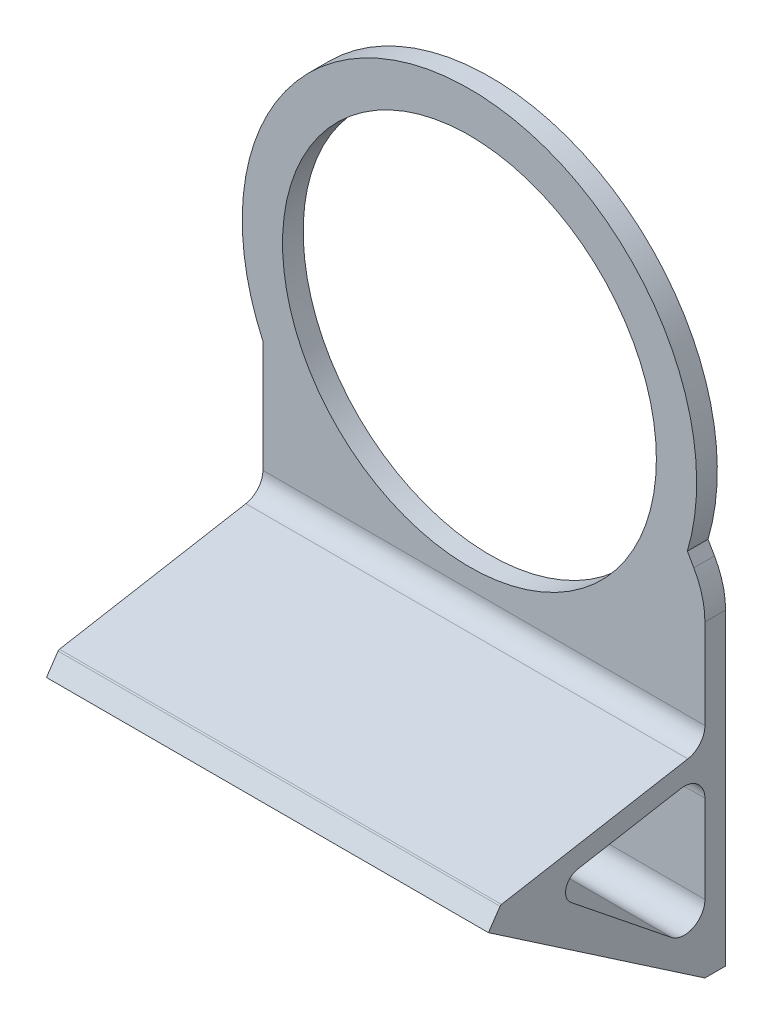
SolidWorks part; units mm, degrees
ref_plane "Plan de face" through (0, 0, 0) normal (0, 0, 1) x (1, 0, 0)
ref_plane "Plan de dessus" through (0, 0, 0) normal (0, 1, 0) x (1, 0, 0)
ref_plane "Plan de droite" through (0, 0, 0) normal (1, 0, 0) x (0, 0, -1)
sketch "Esquisse1" plane through (0, 0, 0) normal (0, 0, 1) x (1, 0, 0)
  circle A0 centre (0, 0) radius 55
  circle A1 centre (0, 0) radius 45.25
  dimension "D1" = 110
  dimension "D2" = 90.5
extrude "Boss.-Extru.1" add sketch "Esquisse1" along normal blind 5
sketch "Esquisse2" plane through (0, 0, 0) normal (0, 0, -1) x (-1, 0, 0)
  line L0 (0, 0) -> (0, -89.0055) construction
  line L1 (-50, -22.9129) -> (-50, -102.9129)
  line L2 (50, -22.9129) -> (50, -102.9129)
  line L3 (-50, -102.9129) -> (50, -102.9129)
  circle A0 centre (0, 0) radius 55 construction
  arc A1 (-50, -22.9129) -> (50, -22.9129) centre (0, 0) ccw
  dimension "D1" = 50
  dimension "D2" = 80
extrude "Boss.-Extru.2" add sketch "Esquisse2" against normal blind 5
sketch "Esquisse3" plane through (0, 0, 0) normal (1, 0, 0) x (0, 0, -1)
  line L0 (-5, -102.9129) -> (-57.4004, -67.2113)
  line L1 (-57.4004, -67.2113) -> (-54.5851, -63.0792)
  line L3 (-5, -102.9129) -> (-5, -22.9129) construction
  line L4 (-5, -96.8627) -> (-5, -102.9129)
  line L5 (-54.2519, -62.864) -> (-5, -54.1795)
  line L6 (-5, -22.9129) -> (-5, -102.9129) construction
  line L7 (-35.8343, -64.6936) -> (-5, -59.2567)
  line L8 (-37.416, -70.871) -> (-5, -96.8627)
  line L9 (-5, -54.1795) -> (-5, -59.2567)
  arc A0 (-35.8343, -64.6936) -> (-37.416, -70.871) centre (-35.2266, -68.1404) ccw
  arc A2 (-54.5851, -63.0792) -> (-54.2519, -62.864) centre (-54.1633, -63.3666) cw
  point P15 (-43.4464, -66.0358)
  point P18 (-54.2404, -62.8619)
  dimension "D5" = 3.5
  dimension "D1" = 5
  dimension "D2" = 60
  dimension "D3" = 50
  dimension "D4" = 5
  dimension "D6" = 100
extrude "Boss.-Extru.3" add sketch "Esquisse3" along normal up to surface and the other way up to surface up to face at (50, -62.9129, 2.5) other way up to face at (-50, -62.9129, 2.5)
fillet "Congé1" radius 5 1 edges at (0, -59.2567, 5)
fillet "Congé2" radius 5 1 edges at (0, -54.1795, 5)
fillet "Congé3" radius 5 1 edges at (0, -96.8627, 5)
sketch "Esquisse5" plane through (50, 0, 0) normal (1, 0, 0) x (0, 0, -1)
  line L0 (-13.1278, -90.3457) -> (-37.416, -70.871) construction
  line L1 (-35.8343, -64.6936) -> (-10.8682, -60.2914) construction
  line L2 (-5, -65.2154) -> (-5, -86.4448) construction
  line L3 (-35.8343, -64.6936) -> (-10.8682, -60.2914)
  line L4 (-5, -65.2154) -> (-5, -86.4448)
  line L5 (-13.1278, -90.3457) -> (-37.416, -70.871)
  line L8 (-9.1318, -54.9081) -> (-54.2519, -62.864)
  line L10 (-54.5851, -63.0792) -> (-57.4004, -67.2113)
  line L11 (-57.4004, -67.2113) -> (-5, -102.9129)
  line L12 (-5, -102.9129) -> (0, -102.9129)
  line L13 (0, -102.9129) -> (0, -22.9129)
  line L14 (0, -22.9129) -> (-5, -22.9129)
  line L15 (-5, -22.9129) -> (-5, -49.984)
  line L16 (-9.1318, -54.9081) -> (-54.2519, -62.864)
  line L18 (-54.5851, -63.0792) -> (-57.4004, -67.2113)
  line L19 (-57.4004, -67.2113) -> (-5, -102.9129)
  line L20 (-5, -102.9129) -> (0, -102.9129)
  line L21 (0, -102.9129) -> (0, -22.9129)
  line L22 (0, -22.9129) -> (-5, -22.9129)
  line L23 (-5, -22.9129) -> (-5, -49.984)
  arc A0 (-35.8343, -64.6936) -> (-37.416, -70.871) centre (-35.2266, -68.1404) ccw construction
  arc A1 (-5, -65.2154) -> (-10.8682, -60.2914) centre (-10, -65.2154) ccw construction
  arc A2 (-9.1318, -54.9081) -> (-5, -49.984) centre (-10, -49.984) ccw
  arc A3 (-54.2519, -62.864) -> (-54.5851, -63.0792) centre (-54.1633, -63.3666) ccw
  arc A4 (-9.1318, -54.9081) -> (-5, -49.984) centre (-10, -49.984) ccw
  arc A6 (-13.1278, -90.3457) -> (-5, -86.4448) centre (-10, -86.4448) ccw construction
  arc A7 (-35.8343, -64.6936) -> (-37.416, -70.871) centre (-35.2266, -68.1404) ccw
  arc A8 (-5, -65.2154) -> (-10.8682, -60.2914) centre (-10, -65.2154) ccw
  arc A9 (-13.1278, -90.3457) -> (-5, -86.4448) centre (-10, -86.4448) ccw
  arc A12 (-54.2519, -62.864) -> (-54.5851, -63.0792) centre (-54.1633, -63.3666) ccw
  dimension "D1" = 0
extrude "Boss.-Extru.4" add sketch "Esquisse5" along normal blind 7
sketch "Esquisse6" plane through (0, 0, 5) normal (0, 0, 1) x (1, 0, 0)
  line L0 (57, -22.9129) -> (52.7537, -15.558)
  line L1 (57, -22.9129) -> (50, -22.9129) construction
  line L2 (57, -22.9129) -> (50, -22.9129)
  arc A0 (50, -22.9129) -> (-50, -22.9129) centre (0, 0) ccw construction
  arc A1 (50, -22.9129) -> (52.7537, -15.558) centre (0, 0) ccw
  dimension "D1" = 60
extrude "Boss.-Extru.5" add sketch "Esquisse6" against normal through all
fillet "Congé7" radius 20 1 edges at (57, -22.9129, 2.5)
